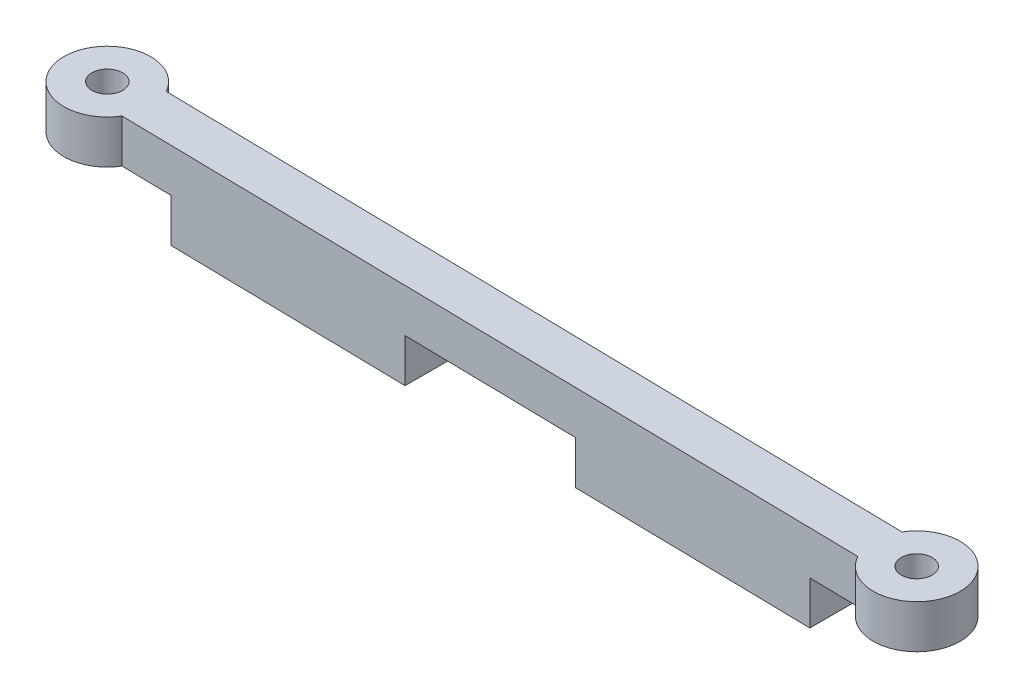
SolidWorks part; units mm, degrees
ref_plane "Front Plane" through (0, 0, 0) normal (0, 0, 1) x (1, 0, 0)
ref_plane "Top Plane" through (0, 0, 0) normal (0, 1, 0) x (1, 0, 0)
ref_plane "Right Plane" through (0, 0, 0) normal (1, 0, 0) x (0, 0, -1)
sketch "Sketch2" plane through (0, 0, 0) normal (0, 1, 0) x (1, 0, 0)
  line L0 (0, 0) -> (120.65, -2.1964)
  line L1 (120.65, -2.1964) -> (120.65, 0.9786)
  line L2 (120.65, 0.9786) -> (0, 3.175)
  line L3 (0, 3.175) -> (0, -3.175)
  line L4 (0, -3.175) -> (120.65, -5.3714)
  circle A0 centre (0, 0) radius 2.2479
  circle A1 centre (0, 0) radius 3.175
  circle A2 centre (0, 0) radius 6.35
  circle A3 centre (120.65, -2.1964) radius 2.2479
  circle A4 centre (120.65, -2.1964) radius 3.175
  circle A5 centre (120.65, -2.1964) radius 6.35
  dimension "D1" = 4.4958
  dimension "D2" = 6.35
  dimension "D3" = 12.7
  dimension "D4" = 4.4958
  dimension "D5" = 6.35
  dimension "D6" = 12.7
  dimension "D7" = 120.65
extrude "Boss-Extrude2" add sketch "Sketch2" along normal blind 12.7 contours L3 A1 A0 | L0 A1 L2 L3 A0 | L3 A1 L0 A0 | L0 A2 L2 A1 | L2 A2 L4 A1 | L4 A2 L0 A1 | A5 L2 A2 L0 | A5 L0 A2 L4 | L2 A5 L0 A4 | L0 A5 L4 A4 | L1 A4 L0 A3 | L4 A4 L1 A3 L0 | L4 A5 L2 A4
sketch "Sketch3" plane through (0, 0, 0) normal (0, -1, 0) x (1, 0, 0)
  line L0 (0, 0) -> (12.7, 0.2367) construction
  line L1 (12.7, 0.2367) -> (12.7, 3.4062) construction
  line L2 (5.4409, 3.274) -> (115.0936, 5.2703) construction
  line L10 (120.65, 2.1964) -> (107.95, 1.9674) construction
  line L11 (12.7, 3.4062) -> (0, 3.4062)
  line L12 (12.7, 3.4062) -> (12.7, -6.35)
  line L13 (12.7, -6.35) -> (0, -6.35)
  line L14 (0, 3.4062) -> (0, -6.35)
  line L15 (120.65, 2.1964) -> (107.95, 1.9674) construction
  line L16 (107.95, 1.9674) -> (107.95, -1.2098) construction
  line L21 (115.2091, -1.0776) -> (5.5564, -3.0738) construction
  line L23 (107.95, -1.2098) -> (120.65, -1.2098)
  line L24 (107.95, -1.2098) -> (107.95, 8.5464)
  line L25 (107.95, 8.5464) -> (120.65, 8.5464)
  line L26 (120.65, -1.2098) -> (120.65, 8.5464)
  circle A0 centre (0, 0) radius 6.35
  circle A1 centre (120.65, 2.1964) radius 6.35
  circle M2 centre (120.65, 2.1964) radius 2.2479
  arc M3 (115.2091, -1.0776) -> (115.0936, 5.2703) centre (120.65, 2.1964) ccw
  line M4 (115.0936, 5.2703) -> (5.4409, 3.274)
  arc M5 (5.4409, 3.274) -> (5.5564, -3.0738) centre (0, 0) ccw
  line M6 (5.5564, -3.0738) -> (115.2091, -1.0776)
  circle M7 centre (0, 0) radius 2.2479
  dimension "D1" = 12.7
  dimension "D2" = 12.7
extrude "Cut-Extrude1" cut sketch "Sketch3" against normal blind 6.35 contours L26 L23 M3 M2 | A0 L12 M6 M4 | A0 L11 L14 M5 M7 | L14 L11 M5 M7
sketch "Sketch4" plane through (0, 0, 0) normal (0, -1, 0) x (1, 0, 0)
  line L5 (47.625, 4.042) -> (47.625, -2.308)
  line L6 (12.7, 3.4062) -> (107.95, 5.1402) construction
  line L7 (107.95, -1.2098) -> (12.7, -2.9438) construction
  line L8 (47.625, -2.308) -> (73.025, -1.8456)
  line L9 (73.025, -1.8456) -> (73.025, 4.5044)
  line L10 (73.025, 4.5044) -> (47.625, 4.042)
  line L11 (12.7, 3.4062) -> (12.7, -2.9438) construction
  dimension "D1" = 25.4
  dimension "D2" = 34.925
extrude "Cut-Extrude2" cut sketch "Sketch4" against normal blind 6.35
